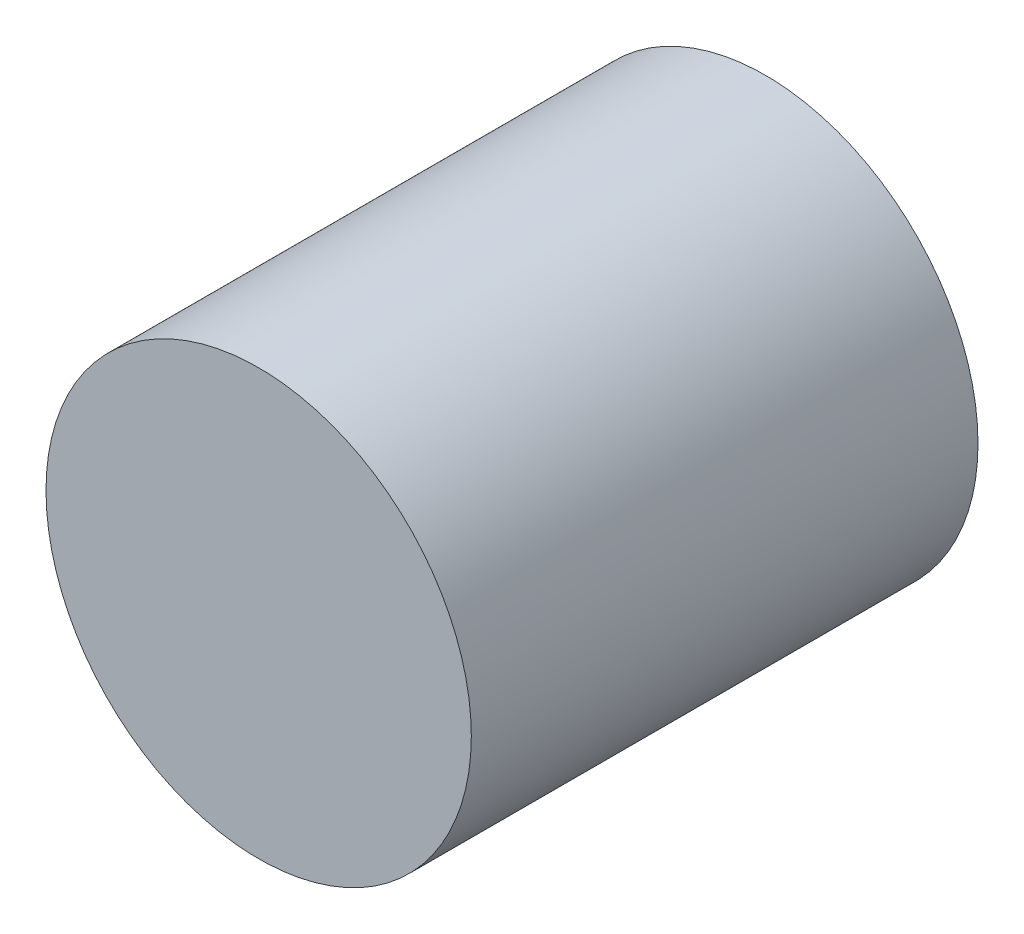
SolidWorks part; units mm, degrees
ref_plane "Front Plane" through (0, 0, 0) normal (0, 0, 1) x (1, 0, 0)
ref_plane "Top Plane" through (0, 0, 0) normal (0, 1, 0) x (1, 0, 0)
ref_plane "Right Plane" through (0, 0, 0) normal (1, 0, 0) x (0, 0, -1)
sketch "Sketch1" plane through (0, 0, 0) normal (0, 0, 1) x (1, 0, 0)
  circle A0 centre (0, 0) radius 13.85
  dimension "D1" = 27.7
extrude "Boss-Extrude1" add sketch "Sketch1" along normal blind 33
